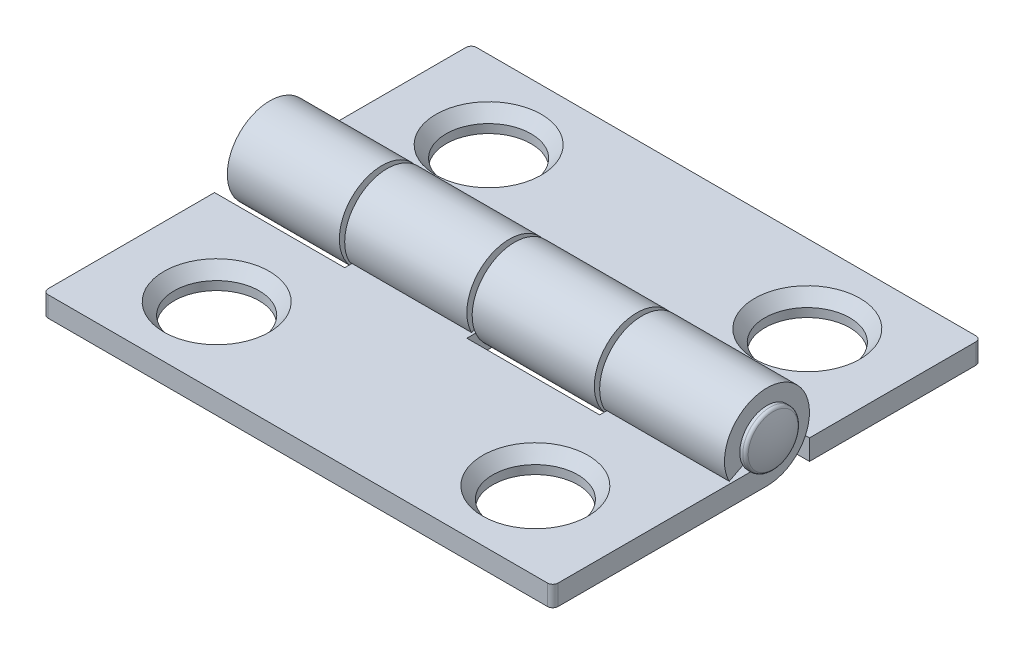
SolidWorks part; units mm, degrees
ref_plane "Front Plane" through (0, 0, 0) normal (0, 0, 1) x (1, 0, 0)
ref_plane "Top Plane" through (0, 0, 0) normal (0, 1, 0) x (1, 0, 0)
ref_plane "Right Plane" through (0, 0, 0) normal (1, 0, 0) x (0, 0, -1)
sketch "Sketch1" plane through (0, 0, 0) normal (0, 1, 0) x (1, 0, 0)
  line L0 (-19.05, 0) -> (19.05, 0) construction
  line L1 (-19.05, -16.002) -> (-19.05, 16.002) construction
  line L2 (11.9062, 10.16) -> (11.9062, -10.16) construction
  line L3 (-11.9062, -16.002) -> (11.9062, -16.002) construction
  line L4 (0, 0) -> (0, -16.002) construction
  line L5 (11.9062, -6.985) -> (11.9062, -13.335) construction
  line L7 (-11.9062, 10.16) -> (11.9062, 10.16) construction
  line L8 (-11.9062, 10.16) -> (-11.9062, -10.16) construction
  line L9 (-11.9062, -10.16) -> (11.9062, -10.16) construction
  line L10 (11.9062, 10.16) -> (11.9062, -10.16) construction
  line L11 (15.0813, -10.16) -> (8.7312, -10.16) construction
  line L12 (-11.9062, 10.16) -> (11.9062, -10.16) construction
  line L13 (-11.9062, -10.16) -> (11.9062, 10.16) construction
  circle A0 centre (11.9062, -10.16) radius 3.937 construction
  point P4 (0, 0)
  point P8 (-19.05, 0)
  point P10 (8.7312, 10.16)
  point P14 (15.0813, -10.16)
  point P18 (8.7312, -10.16)
  point P21 (11.9062, -10.16)
  point P25 (11.9063, 0)
  point P26 (11.9062, -10.16)
  point P27 (11.9062, -6.985)
  point P28 (11.9062, -13.335)
  point P29 (15.0813, 10.16)
  point P31 (-19.05, -16.002)
  point P32 (-11.9062, 10.16)
  point P33 (11.9062, -10.16)
  point P34 (-19.05, 16.002)
  point P38 (11.9062, -10.16)
  dimension "C'Sink Diameter" = 7.874
  dimension "Door Leaf Height" = 38.1
  dimension "Overall Width" = 32.004
  dimension "Hole Spacing" = 23.8125
  dimension "Hole Diameter" = 6.35
  dimension "Hole Spacing 2" = 20.32
  dimension "Frame Leaf Height" = 38.1
  dimension "Door Leaf Width" = 16.002
  dimension "Frame Leaf Width" = 16.002
  dimension "Hole Offset" = 7.1438
sketch "Sketch2" plane through (0, 0, 0) normal (1, 0, 0) x (0, 0, -1)
  line L2 (0, -3.175) -> (0, -1.651) construction
  line L4 (0, 1.651) -> (0, -1.651) construction
  circle A0 centre (0, 0) radius 3.175 construction
  circle A1 centre (0, 0) radius 2.032 construction
  point P8 (0, 0)
  dimension "Leaf OD" = 6.35
  dimension "Pin Head Diameter" = 4.064
  dimension "Leaf Thickness" = 1.524
  dimension "Pin Diameter" = 3.302
sketch "Sketch3" plane through (0, 0, 0) normal (1, 0, 0) x (0, 0, -1)
  line L3 (0, 0) -> (-3.175, -1.651) construction
  line L4 (0, -3.175) -> (-16.002, -3.175)
  line L5 (-16.002, -3.175) -> (-16.002, -1.651)
  line L7 (-16.002, -1.651) -> (0, -1.651)
  line L8 (-16.002, 0) -> (16.002, 0) construction
  line L9 (-1.4648, -0.7617) -> (-2.8169, -1.4648)
  line L11 (-3.175, 0) -> (-3.175, -1.651) construction
  circle A4 centre (0, 0) radius 1.651 construction
  circle A5 centre (0, 0) radius 3.175 construction
  arc A8 (-1.4648, -0.7617) -> (0, -1.651) centre (0, 0) cw
  arc A9 (-2.8169, -1.4648) -> (0, -3.175) centre (0, 0) cw
  point P0 (-2.8169, -1.4648)
  point P13 (-1.4648, -0.7617)
extrude "Boss-Extrude1" add sketch "Sketch3" along normal mid plane 38.1
sketch "Sketch4" plane through (0, 0, 0) normal (0, 1, 0) x (1, 0, 0)
  line L0 (-19.05, -3.175) -> (19.05, -3.175) construction
  line L1 (-19.05, -3.175) -> (19.05, -3.175) construction
  line L2 (19.05, 3.175) -> (-19.05, 3.175) construction
  line L3 (19.05, 3.175) -> (-19.05, 3.175) construction
  line L4 (0, -3.175) -> (0, 3.175)
  line L6 (0, 3.175) -> (9.525, 3.175)
  line L7 (9.525, -3.175) -> (0, -3.175)
  line L8 (9.525, 3.175) -> (9.525, -3.175)
  dimension "D1" = 9.525
extrude "Cut-Extrude1" cut sketch "Sketch4" against normal through all both and the other way through all
pattern_linear "LPattern1" count 2 spacing 19.05 along (-1, 0, 0) of "Cut-Extrude1"
sketch "Sketch5" plane through (0, -1.651, 0) normal (0, 1, 0) x (1, 0, 0)
  line L0 (-9.525, -3.175) -> (0, -3.175) construction
  line L1 (-9.525, 3.175) -> (-9.3266, 3.175)
  line L2 (-9.525, 3.175) -> (-9.525, -3.175)
  line L3 (-9.525, -3.175) -> (-9.3266, -3.175)
  line L4 (-9.3266, 3.175) -> (-9.3266, -3.175)
  line L5 (9.525, 3.175) -> (9.525, -3.175) construction
  line L6 (0, 3.175) -> (-0.1984, 3.175)
  line L7 (0, 3.175) -> (0, -3.175)
  line L8 (0, -3.175) -> (-0.1984, -3.175)
  line L9 (-0.1984, 3.175) -> (-0.1984, -3.175)
  line L10 (9.525, 3.175) -> (9.7234, 3.175)
  line L11 (9.525, 3.175) -> (9.525, -3.175)
  line L12 (9.525, -3.175) -> (9.7234, -3.175)
  line L13 (9.7234, 3.175) -> (9.7234, -3.175)
  line L14 (9.525, -3.175) -> (19.05, -3.175) construction
  line L15 (19.05, 3.175) -> (9.525, 3.175) construction
  dimension "D1" = 0.1984
extrude "Cut-Extrude2" cut sketch "Sketch5" against normal through all both and the other way through all
sketch "Sketch6" plane through (0, -1.651, 0) normal (0, 1, 0) x (1, 0, 0)
  line L0 (11.9062, -10.16) -> (-11.9062, -10.16) construction
  line L1 (11.9062, -10.16) -> (11.9062, -16.002) construction
  line L2 (-11.9062, -10.16) -> (-11.9062, -16.002) construction
  line L3 (11.9062, -10.16) -> (13.4938, -12.9096) construction
  circle A0 centre (11.9062, -10.16) radius 3.175
  circle A3 centre (-11.9062, -10.16) radius 3.175
  point P7 (13.4938, -12.9096)
  dimension "D1" = 30
extrude "Cut-Extrude3" cut sketch "Sketch6" against normal through all
sketch "Sketch7" plane through (0, -1.651, 0) normal (0, 1, 0) x (1, 0, 0)
  circle A0 centre (-11.9062, -10.16) radius 3.937
  circle A1 centre (11.9062, -10.16) radius 3.937
  circle A2 centre (11.9062, -10.16) radius 3.937 construction
extrude "Cut-Extrude4" cut sketch "Sketch7" against normal through all draft 41
fillet "Fillet1" radius 0.3969 2 edges at (19.05, -2.413, 16.002) (-19.05, -2.413, 16.002)
pattern_circular "CirPattern1" count 2 over 360 about axis through (0, 0, 0) along (0, 1, 0) of bodies 111 107
sketch "Sketch8" plane through (0, 0, 0) normal (1, 0, 0) x (0, 0, -1)
  circle A0 centre (0, 0) radius 1.651
  dimension "D1" = 3.302
extrude "Boss-Extrude2" add sketch "Sketch8" along normal mid plane 38.1 separate body
sketch "Sketch9" plane through (0, 0, 0) normal (0, 0, 1) x (1, 0, 0)
  line L2 (19.05, 2.032) -> (19.05, -2.032) construction
  line L3 (19.05, 0) -> (19.8438, 0) construction
  line L4 (0, -2.032) -> (0, 2.032) construction
  line L7 (19.05, 2.032) -> (19.05, 0)
  line L8 (19.05, 0) -> (19.8438, 0)
  line L9 (19.05, -1.651) -> (19.05, -3.175) construction
  line L10 (0, -2.032) -> (0, 2.032) construction
  line L11 (-19.05, 1.651) -> (-19.05, 3.175) construction
  line L12 (19.05, 2.032) -> (19.2729, 2.032)
  line L13 (19.05, 1.651) -> (19.05, 3.175) construction
  line L14 (-19.05, 0) -> (-19.8438, 0) construction
  line L15 (-19.05, 2.032) -> (-19.2729, 2.032)
  line L16 (-19.05, 0) -> (-19.8438, 0)
  line L17 (-19.05, 2.032) -> (-19.05, 0)
  line L21 (19.05, 1.651) -> (9.7234, 1.651) construction
  line L22 (19.05, 3.175) -> (9.7234, 3.175) construction
  line L24 (19.05, 0) -> (-19.05, 0) construction
  arc A0 (19.05, 2.032) -> (19.05, -2.032) centre (16.8459, 0) cw construction
  arc A4 (19.5112, 1.8658) -> (19.8438, 0) centre (14.4434, 0) cw
  arc A5 (19.2729, 2.032) -> (19.5112, 1.8658) centre (19.2729, 1.778) cw
  arc A8 (-19.2729, 2.032) -> (-19.5112, 1.8658) centre (-19.2729, 1.778) ccw
  arc A9 (-19.5112, 1.8658) -> (-19.8438, 0) centre (-14.4434, 0) ccw
  point P12 (19.05, 0)
  point P20 (19.4469, 0)
  point P29 (19.4469, 2.032)
  point P36 (19.05, 2.413)
  point P41 (-19.05, 2.413)
  point P42 (-19.4469, 2.032)
  point P43 (-19.4469, 0)
  dimension "D2" = 0.254
  dimension "D1" = 0.7937
revolve "Revolve1" add sketch "Sketch9" angle 360 about L24
sketch "Sketch10" plane through (0, -3.175, 0) normal (0, -1, 0) x (1, 0, 0)
  line L0 (0, -3.175) -> (9.525, -3.175) construction
  line L1 (-18.0975, -3.175) -> (-19.05, -3.175)
  line L2 (-18.0975, -3.175) -> (-18.0975, 3.175)
  line L3 (-18.0975, 3.175) -> (-19.05, 3.175)
  line L4 (-19.05, -3.175) -> (-19.05, 3.175)
  line L5 (-19.05, 3.175) -> (19.05, 3.175) construction
  dimension "D1" = 0.9525
extrude "Cut-Extrude5" cut sketch "Sketch10" against normal through all
chamfer "Chamfer1" distance 0.1651 angle 45 1 edges at (-19.05, 0, -1.651)
other "Save Bodies1"
equation "\"D1@Boss-Extrude1\" = \"Door Leaf Height@Sketch1\""
equation "\"D1@Sketch4\"=\"Door Leaf Height@Sketch1\" / 4"
equation "\"D3@LPattern1\"= \"D1@Sketch4\" * 2"
equation "\"D1@Sketch8\" = \"Pin Diameter@Sketch2\""
equation "\"D1@Boss-Extrude2\" = \"Door Leaf Height@Sketch1\""
equation "\"D1@Sketch10\"=\"D1@Sketch4\"*.1"
equation "\"D1@Chamfer1\"=\"Pin Diameter@Sketch2\"*.05"
